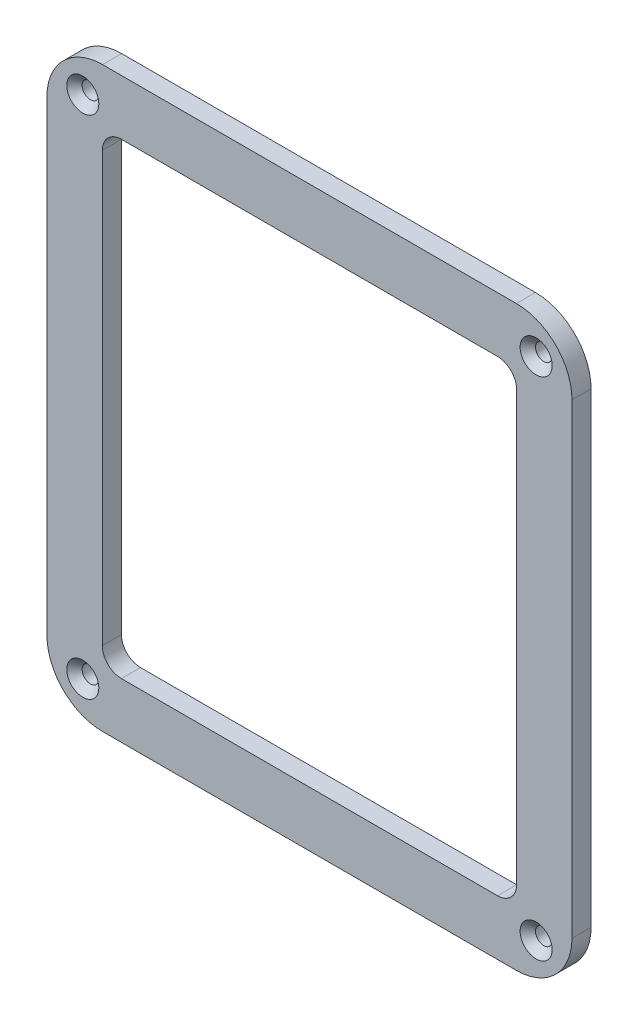
SolidWorks part; units mm, degrees
material "Acrylic (Medium-high impact)"
ref_plane "Front Plane" through (0, 0, 0) normal (0, 0, 1) x (1, 0, 0)
ref_plane "Top Plane" through (0, 0, 0) normal (0, 1, 0) x (1, 0, 0)
ref_plane "Right Plane" through (0, 0, 0) normal (1, 0, 0) x (0, 0, -1)
sketch "Sketch1" plane through (0, 0, 0) normal (0, 0, 1) x (1, 0, 0)
  line L0 (-51.5878, 57.0878) -> (-43.3891, 48.8891) construction
  line L1 (39.4, -48.925) -> (-39.4, -48.925)
  line L2 (43.4, -44.925) -> (43.4, 44.925)
  line L3 (39.4, 48.925) -> (-39.4, 48.925)
  line L4 (-43.4, -44.925) -> (-43.4, 44.925)
  line L5 (43.4, -48.925) -> (-43.4, 48.925) construction
  line L6 (43.4, 48.925) -> (-43.4, -48.925) construction
  line L7 (43.35, -60.5) -> (-43.35, -60.5)
  line L8 (55, -48.85) -> (55, 48.85)
  line L9 (43.35, 60.5) -> (-43.35, 60.5)
  line L10 (-55, -48.85) -> (-55, 48.85)
  line L11 (55, -60.5) -> (-55, 60.5) construction
  line L12 (55, 60.5) -> (-55, -60.5) construction
  line L13 (0, 0) -> (-50000, 0) construction
  line L14 (0, 0) -> (0, 50000) construction
  line L19 (-39.5, -50.5) -> (39.5, -50.5) construction
  line L20 (-45, -45) -> (-45, 45) construction
  line L21 (-39.5, 50.5) -> (39.5, 50.5) construction
  line L22 (45, -45) -> (45, 45) construction
  line L23 (-45, -50.5) -> (45, 50.5) construction
  line L24 (-45, 50.5) -> (45, -50.5) construction
  arc A0 (55, 48.85) -> (43.35, 60.5) centre (43.35, 48.85) ccw
  arc A1 (43.35, -60.5) -> (55, -48.85) centre (43.35, -48.85) ccw
  arc A2 (-43.35, -60.5) -> (-55, -48.85) centre (-43.35, -48.85) cw
  arc A3 (-43.35, 60.5) -> (-55, 48.85) centre (-43.35, 48.85) ccw
  arc A4 (43.4, 44.925) -> (39.4, 48.925) centre (39.4, 44.925) ccw
  arc A5 (39.4, -48.925) -> (43.4, -44.925) centre (39.4, -44.925) ccw
  arc A6 (-39.4, -48.925) -> (-43.4, -44.925) centre (-39.4, -44.925) cw
  arc A7 (-39.4, 48.925) -> (-43.4, 44.925) centre (-39.4, 44.925) ccw
  circle A8 centre (-47.4884, 52.9884) radius 1.75
  arc A12 (39.5, 50.5) -> (45, 45) centre (39.5, 45) cw construction
  arc A13 (39.5, -50.5) -> (45, -45) centre (39.5, -45) ccw construction
  arc A14 (-39.5, -50.5) -> (-45, -45) centre (-39.5, -45) cw construction
  arc A15 (-45, 45) -> (-39.5, 50.5) centre (-39.5, 45) cw construction
  circle A16 centre (47.4884, 52.9884) radius 1.75
  circle A17 centre (47.4884, -52.9884) radius 1.75
  circle A18 centre (-47.4884, -52.9884) radius 1.75
  point P0 (0, 0)
  point P6 (0, 0)
  point P38 (-47.4884, 52.9884)
  point P47 (47.4884, 52.9884)
  point P54 (0, 0)
  point P73 (-47.4884, 52.9884)
  dimension "D5" = 11.65
  dimension "D6" = 4
  dimension "D8" = 3.5
  dimension "D11" = 5.5
  dimension "D1" = 86.8
  dimension "D2" = 97.85
  dimension "D3" = 121
  dimension "D4" = 110
  dimension "D9" = 101
  dimension "D10" = 90
extrude "Boss-Extrude1" add sketch "Sketch1" along normal blind 4
hole_wizard "CSK for M3 Hex Socket Countersunk Cap Screw1" positions "Sketch2" profile "Sketch3" countersink size "M3" standard "ISO" end condition through all
sketch "Sketch2" plane through (0, 0, 4) normal (0, 0, 1) x (1, 0, 0)
  point P0 (-47.4884, -52.9884)
  point P3 (47.4884, -52.9884)
  point P6 (47.4884, 52.9884)
  point P9 (-47.4884, 52.9884)
sketch "Sketch3" plane through (-47.4884, -52.9884, 4) normal (1, 0, 0) x (0, -1, 0)
  line L0 (0, 0) -> (0, 4)
  line L1 (0, 4) -> (1.7, 4)
  line L2 (1.7, 4) -> (1.7, 1.66)
  line L3 (1.7, 1.66) -> (3.36, 0)
  line L5 (3.36, 0) -> (0, 0)
  line L6 (-1.7, 1.66) -> (-3.36, 0) construction
  line L11 (0, -6.35) -> (0, 107.95) construction
  dimension "Thru Hole Dia." = 3.4
  dimension "Thru Hole Depth" = 4
  dimension "Near C'Sink Dia." = 6.72
  dimension "Near C'Sink Angle" = 90
